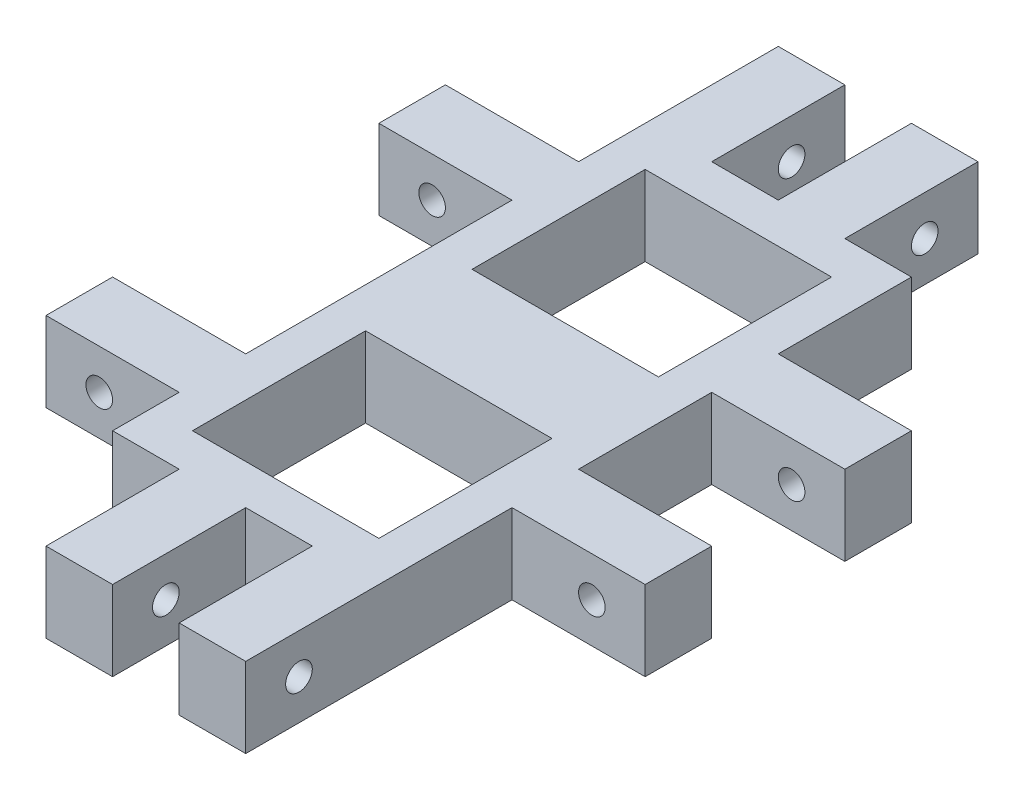
SolidWorks part; units mm, degrees
ref_plane "Plano frontal" through (0, 0, 0) normal (0, 0, 1) x (1, 0, 0)
ref_plane "Plano superior" through (0, 0, 0) normal (0, 1, 0) x (1, 0, 0)
ref_plane "Plano direito" through (0, 0, 0) normal (1, 0, 0) x (0, 0, -1)
sketch "Esboço1" plane through (0, 0, 0) normal (0, 0, 1) x (1, 0, 0)
  line L1 (-9.5848, 3.9082) -> (10.4152, 3.9082)
  line L2 (-9.5848, 3.9082) -> (-9.5848, -2.0918)
  line L3 (-9.5848, -2.0918) -> (10.4152, -2.0918)
  line L4 (10.4152, 3.9082) -> (10.4152, -2.0918)
  dimension "D1" = 20
  dimension "D2" = 6
extrude "Ressalto-extrusão1" add sketch "Esboço1" along normal blind 40
sketch "Esboço2" plane through (0, 3.9082, 0) normal (0, 1, 0) x (1, 0, 0)
  line L0 (-9.5848, -40) -> (-9.5848, 0) construction
  line L1 (-9.5848, -5) -> (-19.5848, -5)
  line L2 (-9.5848, -5) -> (-9.5848, -10)
  line L3 (-9.5848, -10) -> (-19.5848, -10)
  line L4 (-19.5848, -5) -> (-19.5848, -10)
  line L5 (10.4152, 0) -> (-9.5848, 0) construction
  line L6 (-9.5848, -30) -> (-19.5848, -30)
  line L7 (-9.5848, -30) -> (-9.5848, -35)
  line L8 (-9.5848, -35) -> (-19.5848, -35)
  line L9 (-19.5848, -30) -> (-19.5848, -35)
  line L10 (-9.5848, 0) -> (-4.5848, 0)
  line L11 (-9.5848, 0) -> (-9.5848, 10)
  line L12 (-9.5848, 10) -> (-4.5848, 10)
  line L13 (-4.5848, 0) -> (-4.5848, 10)
  line L14 (-9.5848, -10) -> (10.4152, -10) construction
  line L15 (0.4152, 0) -> (5.4152, 0)
  line L16 (0.4152, 0) -> (0.4152, 10)
  line L17 (0.4152, 10) -> (5.4152, 10)
  line L18 (5.4152, 0) -> (5.4152, 10)
  line L19 (10.4152, -40) -> (10.4152, 0) construction
  line L20 (-9.5848, -30) -> (10.4152, -30) construction
  line L21 (-4.5848, 0) -> (-4.5848, -40) construction
  line L22 (10.4152, -10) -> (20.4152, -10)
  line L23 (10.4152, -10) -> (10.4152, -15)
  line L24 (10.4152, -15) -> (20.4152, -15)
  line L25 (20.4152, -10) -> (20.4152, -15)
  line L26 (10.4152, -30) -> (20.4152, -30)
  line L27 (10.4152, -30) -> (10.4152, -25)
  line L28 (10.4152, -25) -> (20.4152, -25)
  line L29 (20.4152, -30) -> (20.4152, -25)
  line L30 (10.4152, -40) -> (-9.5848, -40) construction
  line L31 (5.4152, 0) -> (5.4152, -40) construction
  line L33 (-4.5848, -40) -> (0.4152, -40)
  line L34 (-4.5848, -40) -> (-4.5848, -50)
  line L35 (-4.5848, -50) -> (0.4152, -50)
  line L36 (0.4152, -40) -> (0.4152, -50)
  line L37 (5.4152, -40) -> (10.4152, -40)
  line L38 (5.4152, -40) -> (5.4152, -50)
  line L39 (5.4152, -50) -> (10.4152, -50)
  line L40 (10.4152, -40) -> (10.4152, -50)
  dimension "D1" = 5
  dimension "D2" = 5
  dimension "D3" = 10
  dimension "D4" = 10
  dimension "D5" = 5
  dimension "D6" = 20
  dimension "D7" = 5
  dimension "D8" = 0
  dimension "D9" = 5
  dimension "D10" = 5
extrude "Ressalto-extrusão2" add sketch "Esboço2" against normal through all
sketch "Esboço3" plane through (0, 0, 30) normal (0, 0, 1) x (1, 0, 0)
  line L0 (10.4152, -2.0918) -> (20.4152, -2.0918) construction
  line L1 (20.4152, -2.0918) -> (20.4152, 3.9082) construction
  circle A0 centre (16.4152, 0.9082) radius 1
  dimension "D3" = 2
  dimension "D1" = 3
  dimension "D2" = 4
extrude "Corte-extrusão1" cut sketch "Esboço3" against normal blind 40
sketch "Esboço4" plane through (-4.5848, 0, 0) normal (-1, 0, 0) x (0, 0, 1)
  circle A0 centre (46, 0.9082) radius 1
  dimension "D3" = 2
  dimension "D1" = 4
  dimension "D2" = 3
extrude "Corte-extrusão2" cut sketch "Esboço4" against normal blind 40
sketch "Esboço5" plane through (0, 0, 35) normal (0, 0, 1) x (1, 0, 0)
  line L0 (-19.5848, -2.0918) -> (-19.5848, 3.9082) construction
  circle A0 centre (-15.5848, 0.9082) radius 1
  dimension "D3" = 2
  dimension "D1" = 4
  dimension "D2" = 3
extrude "Corte-extrusão3" cut sketch "Esboço5" against normal blind 40
sketch "Esboço6" plane through (5.4152, 0, 0) normal (1, 0, 0) x (0, 0, -1)
  circle A0 centre (6, 0.9082) radius 1
  dimension "D3" = 2
  dimension "D1" = 4
  dimension "D2" = 3
extrude "Corte-extrusão4" cut sketch "Esboço6" against normal blind 40
sketch "Esboço7" plane through (0, 3.9082, 0) normal (0, 1, 0) x (1, 0, 0)
  line L0 (-9.5848, -5) -> (-9.5848, 10) construction
  line L1 (-6.5848, -3) -> (7.4152, -3)
  line L2 (-6.5848, -3) -> (-6.5848, -16)
  line L3 (-6.5848, -16) -> (7.4152, -16)
  line L4 (7.4152, -3) -> (7.4152, -16)
  line L5 (10.4152, -10) -> (10.4152, 0) construction
  line L6 (-4.5848, -40) -> (-9.5848, -40) construction
  line L7 (-6.5848, -24) -> (7.4152, -24)
  line L8 (-6.5848, -24) -> (-6.5848, -37)
  line L9 (-6.5848, -37) -> (7.4152, -37)
  line L10 (7.4152, -24) -> (7.4152, -37)
  line L11 (10.4152, -50) -> (10.4152, -30) construction
  line L12 (-9.5848, -30) -> (-9.5848, -10) construction
  line L13 (10.4152, 0) -> (5.4152, 0) construction
  dimension "D1" = 3
  dimension "D2" = 3
  dimension "D3" = 3
  dimension "D4" = 3
  dimension "D5" = 3
  dimension "D6" = 3
  dimension "D7" = 13
  dimension "D8" = 13
extrude "Corte-extrusão5" cut sketch "Esboço7" against normal blind 40
